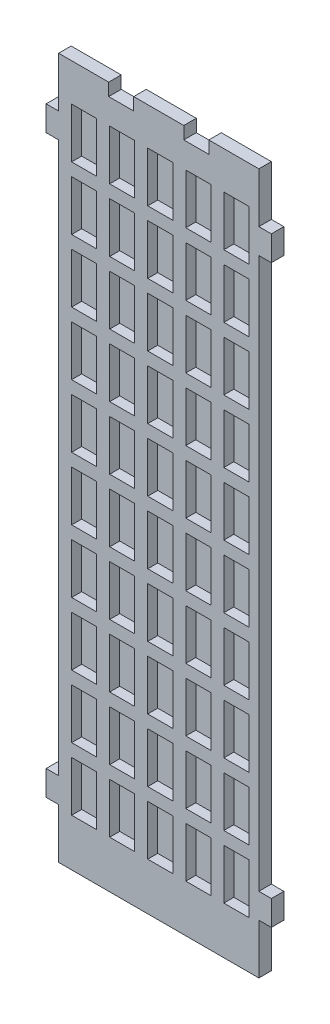
SolidWorks part; units mm, degrees
ref_plane "Front Plane" through (0, 0, 0) normal (0, 0, 1) x (1, 0, 0)
ref_plane "Top Plane" through (0, 0, 0) normal (0, 1, 0) x (1, 0, 0)
ref_plane "Right Plane" through (0, 0, 0) normal (1, 0, 0) x (0, 0, -1)
sketch "Sketch1" plane through (0, 0, 0) normal (0, 0, 1) x (1, 0, 0)
  line L0 (19.05, 0) -> (31.75, 0)
  line L1 (0, 0) -> (12.7, 0)
  line L2 (0, 0) -> (0, -12.7)
  line L3 (0, -177.8) -> (12.7, -177.8)
  line L4 (50.8, -19.05) -> (50.8, -158.75)
  line L5 (38.1, 0) -> (50.8, 0)
  line L6 (12.7, 0) -> (12.7, -3.175)
  line L7 (12.7, -3.175) -> (19.05, -3.175)
  line L8 (19.05, 0) -> (19.05, -3.175)
  line L9 (0, -19.05) -> (0, -158.75)
  line L10 (31.75, 0) -> (31.75, -3.175)
  line L11 (31.75, -3.175) -> (38.1, -3.175)
  line L12 (38.1, 0) -> (38.1, -3.175)
  line L13 (50.8, -12.7) -> (53.975, -12.7)
  line L14 (50.8, -165.1) -> (50.8, -177.8)
  line L15 (50.8, -19.05) -> (53.975, -19.05)
  line L16 (53.975, -12.7) -> (53.975, -19.05)
  line L17 (50.8, -158.75) -> (53.975, -158.75)
  line L18 (38.1, -177.8) -> (50.8, -177.8)
  line L19 (50.8, -165.1) -> (53.975, -165.1)
  line L20 (53.975, -158.75) -> (53.975, -165.1)
  line L21 (12.7, -177.8) -> (38.1, -177.8)
  line L25 (0, -165.1) -> (0, -177.8)
  line L29 (0, -165.1) -> (-3.175, -165.1)
  line L31 (0, -158.75) -> (-3.175, -158.75)
  line L32 (-3.175, -165.1) -> (-3.175, -158.75)
  line L33 (0, -19.05) -> (-3.175, -19.05)
  line L34 (50.8, 0) -> (50.8, -12.7)
  line L35 (0, -12.7) -> (-3.175, -12.7)
  line L36 (-3.175, -19.05) -> (-3.175, -12.7)
  dimension "D3" = 12.7
  dimension "D4" = 6.35
  dimension "D5" = 3.175
  dimension "D6" = 6.35
  dimension "D7" = 3.175
  dimension "D8" = 12.7
  dimension "D9" = 177.8
  dimension "D10" = 6.35
  dimension "D11" = 3.175
  dimension "D12" = 3.175
  dimension "D13" = 6.35
  dimension "D14" = 12.7
  dimension "D15" = 50.8
  dimension "D21" = 3.175
  dimension "D22" = 6.35
  dimension "D23" = 12.7
  dimension "D24" = 12.7
  dimension "D25" = 6.35
  dimension "D26" = 3.175
  dimension "D27" = 3.175
  dimension "D29" = 3.175
  dimension "D30" = 12.7
extrude "Boss-Extrude1" add sketch "Sketch1" along normal blind 3.175
sketch "Sketch2" plane through (0, 0, 3.175) normal (0, 0, 1) x (1, 0, 0)
  line L0 (12.7, -3.175) -> (19.05, -3.175) construction
  line L1 (3.302, -9.525) -> (9.652, -9.525)
  line L2 (3.302, -9.525) -> (3.302, -22.225)
  line L3 (3.302, -22.225) -> (9.652, -22.225)
  line L4 (9.652, -9.525) -> (9.652, -22.225)
  line L5 (3.302, -9.525) -> (9.652, -22.225) construction
  line L6 (3.302, -22.225) -> (9.652, -9.525) construction
  line L7 (0, -19.05) -> (0, -158.75) construction
  point P0 (6.477, -15.875)
  dimension "D1" = 6.35
  dimension "D2" = 12.7
  dimension "D3" = 6.35
  dimension "D4" = 3.302
extrude "Cut-Extrude1" cut sketch "Sketch2" against normal blind 2.54
pattern_linear "LPattern1" count 5 spacing 9.652 along (1, 0, 0) count 10 spacing 15.9512 along (0, -1, 0) of "Cut-Extrude1"
